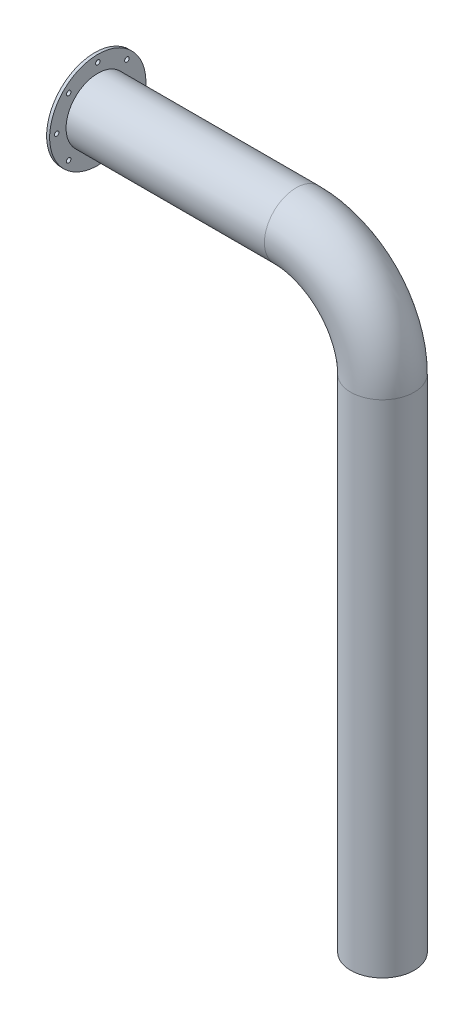
SolidWorks part; units mm, degrees
ref_plane "Front Plane" through (0, 0, 0) normal (0, 0, 1) x (1, 0, 0)
ref_plane "Top Plane" through (0, 0, 0) normal (0, 1, 0) x (1, 0, 0)
ref_plane "Right Plane" through (0, 0, 0) normal (1, 0, 0) x (0, 0, -1)
sketch "Sketch1" plane through (0, 0, 0) normal (1, 0, 0) x (0, 0, -1)
  line L0 (0, 0) -> (0, 109) construction
  circle A0 centre (0, 0) radius 80
  circle A1 centre (0, 0) radius 109 construction
  circle A2 centre (0, 0) radius 127.5
  circle A3 centre (0, 109) radius 6
  circle A4 centre (77.0746, 77.0746) radius 6
  circle A5 centre (109, 0) radius 6
  circle A6 centre (77.0746, -77.0746) radius 6
  circle A7 centre (0, -109) radius 6
  circle A8 centre (-77.0746, -77.0746) radius 6
  circle A9 centre (-109, 0) radius 6
  circle A10 centre (-77.0746, 77.0746) radius 6
  point P23 (0, 0)
  dimension "D1" = 255
  dimension "D2" = 160
  dimension "D3" = 218
  dimension "D4" = 12
  dimension "D5" = 8
extrude "Boss-Extrude1" add sketch "Sketch1" along normal blind 8
sketch "Sketch2" plane through (8, 0, 0) normal (1, 0, 0) x (0, 0, -1)
  circle A0 centre (0, 0) radius 80
  circle A1 centre (0, 0) radius 84
  dimension "D1" = 168
extrude "Boss-Extrude2" add sketch "Sketch2" along normal blind 525.2
sketch "Sketch3" plane through (533.2, 0, 0) normal (1, 0, 0) x (0, 0, -1)
  circle A0 centre (0, 0) radius 80
  circle A1 centre (0, 0) radius 84
  circle A2 centre (0, 0) radius 84
  dimension "D1" = 0
sketch "Sketch4" plane through (0, 0, 0) normal (0, 0, 1) x (1, 0, 0)
  line L0 (533.2, 0) -> (533.2, -228.6) construction
  line L3 (533.2, -228.6) -> (761.8, -228.6) construction
  arc A0 (533.2, 0) -> (761.8, -228.6) centre (533.2, -228.6) cw
  dimension "D1" = 228.6
sweep "Sweep1" add profiles "Sketch3" path "Sketch4"
sketch "Sketch5" plane through (0, -228.6, 0) normal (0, -1, 0) x (1, 0, 0)
  circle A0 centre (761.8, 0) radius 80 construction
  circle A1 centre (761.8, 0) radius 84
  circle A2 centre (761.8, 0) radius 84
  circle A3 centre (761.8, 0) radius 80
  dimension "D1" = 0
extrude "Boss-Extrude3" add sketch "Sketch5" along normal blind 1325.9
